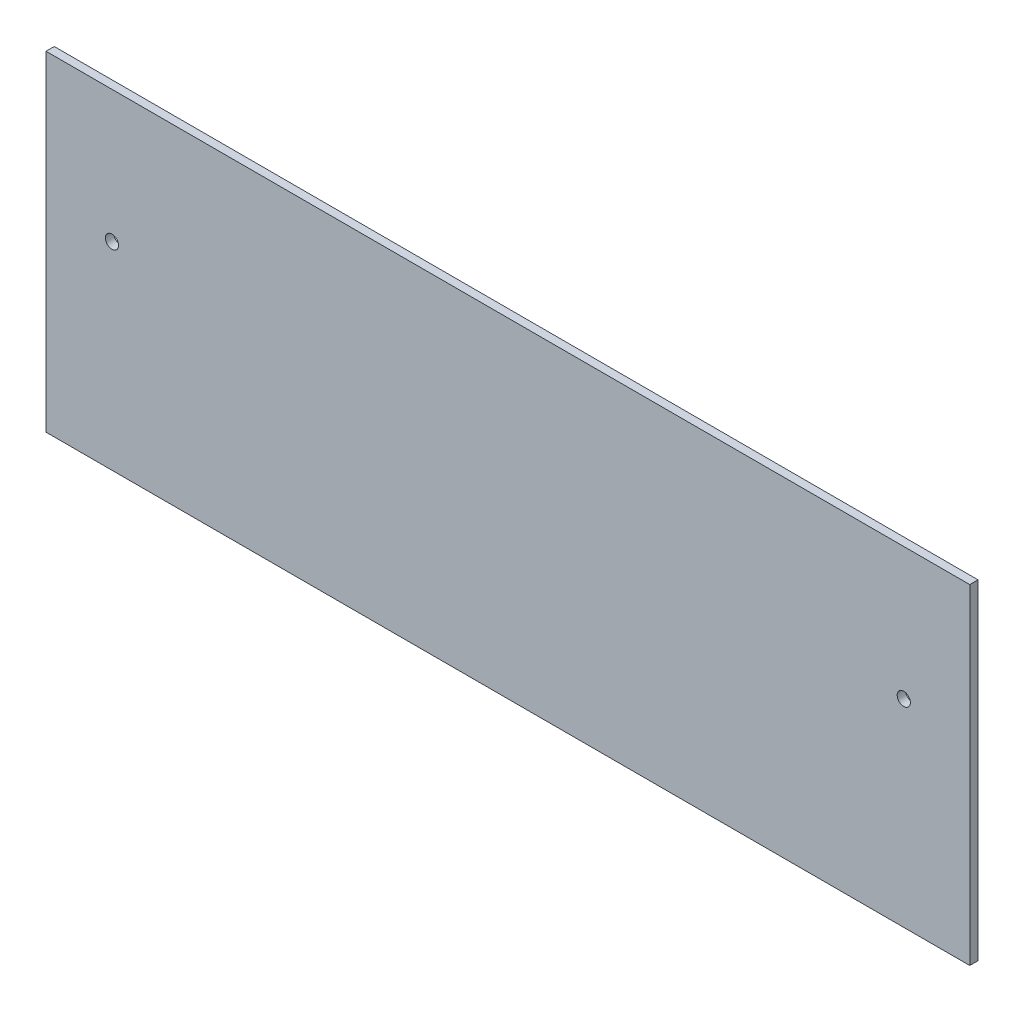
SolidWorks part; units mm, degrees
material "Acrilico (impatto medio-alto)"
ref_plane "Piano frontale" through (0, 0, 0) normal (0, 0, 1) x (1, 0, 0)
ref_plane "Piano superiore" through (0, 0, 0) normal (0, 1, 0) x (1, 0, 0)
ref_plane "Piano destro" through (0, 0, 0) normal (1, 0, 0) x (0, 0, -1)
sketch "Schizzo1" plane through (0, 0, 0) normal (0, 0, 1) x (1, 0, 0)
  line L1 (0, 0) -> (280, 0)
  line L3 (0, 100) -> (280, 100)
  line L14 (0, 0) -> (0, 100)
  line L15 (280, 0) -> (280, 100)
  dimension "D1" = 100
  dimension "D2" = 280
extrude "Estrusione-Estrusione1" add sketch "Schizzo1" along normal blind 2.5
sketch "Schizzo2" plane through (0, 0, 0) normal (0, 0, -1) x (-1, 0, 0)
  circle A0 centre (-20, 60) radius 2
  circle A1 centre (-260, 60) radius 2
  dimension "D1" = 4
extrude "Taglio-Estrusione1" cut sketch "Schizzo2" against normal blind 10
